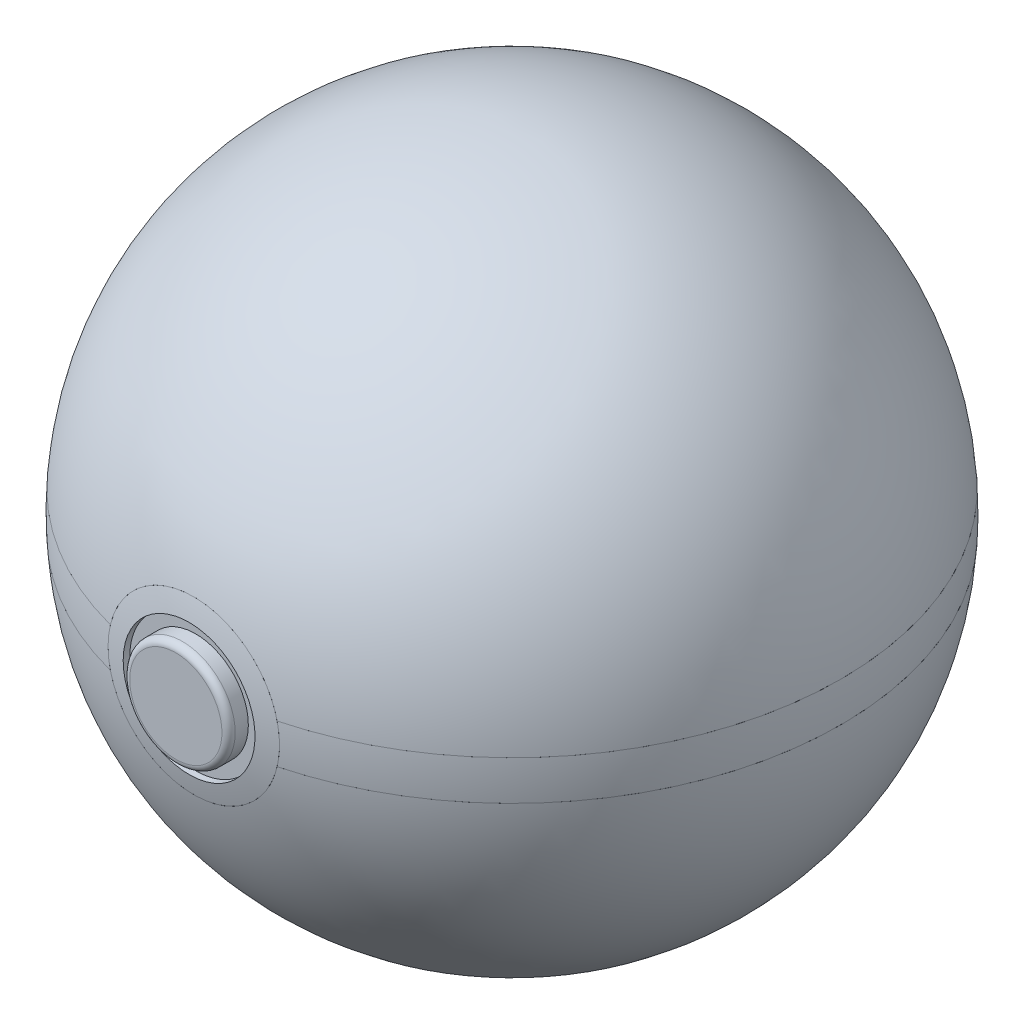
SolidWorks part; units mm, degrees
ref_plane "Front Plane" through (0, 0, 0) normal (0, 0, 1) x (1, 0, 0)
ref_plane "Top Plane" through (0, 0, 0) normal (0, 1, 0) x (1, 0, 0)
ref_plane "Right Plane" through (0, 0, 0) normal (1, 0, 0) x (0, 0, -1)
sketch "Sketch1" plane through (0, 0, 0) normal (0, 0, 1) x (1, 0, 0)
  line L0 (0, -3) -> (0, 3) construction
  line L1 (49.9099, 3) -> (0, 3)
  line L2 (49.9099, -3) -> (0, -3)
  line L5 (0, 50) -> (0, 3)
  line L6 (0, -3) -> (0, -50)
  arc A0 (0, -50) -> (49.9099, -3) centre (0, 0) ccw
  arc A1 (49.9099, 3) -> (0, 50) centre (0, 0) ccw
  point P6 (0, 0)
  dimension "D1" = 100
revolve "Revolve1" add sketch "Sketch1" angle 360 about L0
sketch "Sketch3" plane through (0, 0, 0) normal (0, 0, 1) x (1, 0, 0)
  line L0 (49.9099, 3) -> (0, 3)
  line L1 (0, 3) -> (0, -3)
  line L2 (0, -3) -> (49.9099, -3)
  arc A0 (0, -50) -> (49.9099, -3) centre (0, 0) ccw construction
  arc A1 (49.9099, -3) -> (49.9099, 3) centre (0, 0) ccw
revolve "Revolve2" add sketch "Sketch3" angle 360 about L1
sketch "Sketch4" plane through (0, 0, 0) normal (0, 0, 1) x (1, 0, 0)
  circle A0 centre (0, 0) radius 13
  dimension "D1" = 26
extrude "Cut-Extrude1" cut sketch "Sketch4" along normal blind 70
sketch "Sketch5" plane through (0, 0, 0) normal (0, 0, 1) x (1, 0, 0)
  circle A0 centre (0, 0) radius 13
extrude "Boss-Extrude2" add sketch "Sketch5" along normal up to surface (48.2804 mm away) separate body
sketch "Sketch6" plane through (0, 0, 0) normal (0, 0, 1) x (1, 0, 0)
  circle A0 centre (0, 0) radius 10
  dimension "D1" = 20
extrude "Cut-Extrude2" cut sketch "Sketch6" along normal blind 70
sketch "Sketch7" plane through (0, 0, 0) normal (0, 0, 1) x (1, 0, 0)
  circle A0 centre (0, 0) radius 10
extrude "Boss-Extrude4" add sketch "Sketch7" along normal blind 48 separate body
sketch "Sketch8" plane through (0, 0, 48) normal (0, 0, 1) x (1, 0, 0)
  circle A0 centre (0, 0) radius 8
  dimension "D1" = 16
extrude "Boss-Extrude6" add sketch "Sketch8" along normal blind 3 separate body
fillet "Fillet1" radius 1 1 edges at (8, 0, 51)
